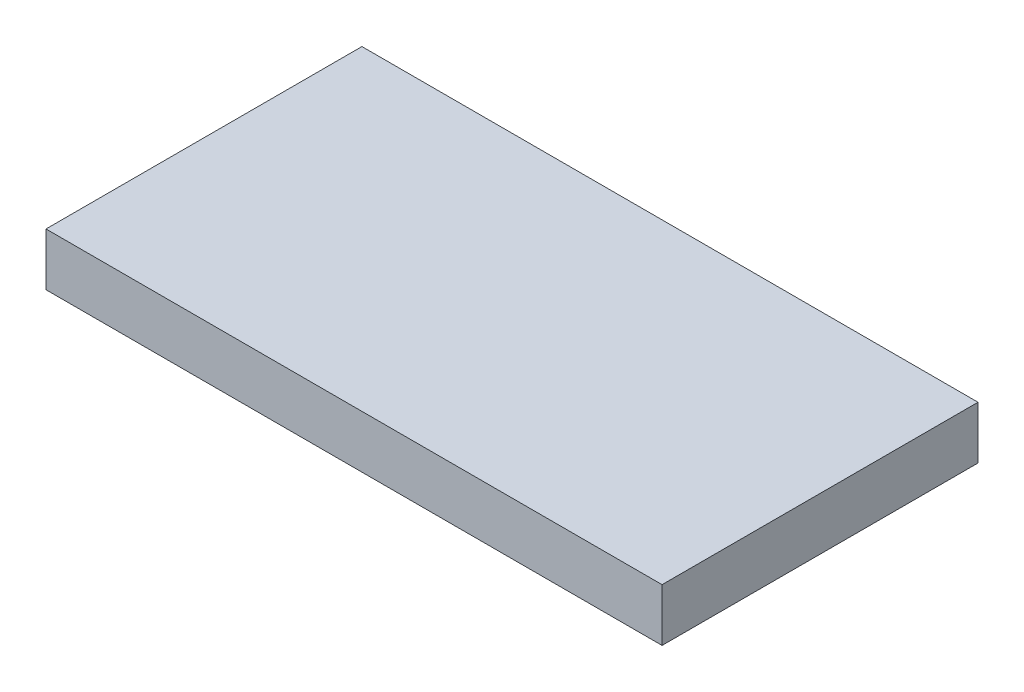
SolidWorks part; units mm, degrees
ref_plane "前视基准面" through (0, 0, 0) normal (0, 0, 1) x (1, 0, 0)
ref_plane "上视基准面" through (0, 0, 0) normal (0, 1, 0) x (1, 0, 0)
ref_plane "右视基准面" through (0, 0, 0) normal (1, 0, 0) x (0, 0, -1)
other "Configuration Table"
sketch "草图1" plane through (0, 0, 0) normal (0, 1, 0) x (1, 0, 0)
  line L1 (0, 0) -> (23.4, 0)
  line L2 (0, 0) -> (0, -12)
  line L3 (0, -12) -> (23.4, -12)
  line L4 (23.4, 0) -> (23.4, -12)
  dimension "D1" = 12
  dimension "D2" = 23.4
extrude "凸台-拉伸1" add sketch "草图1" along normal blind 2
